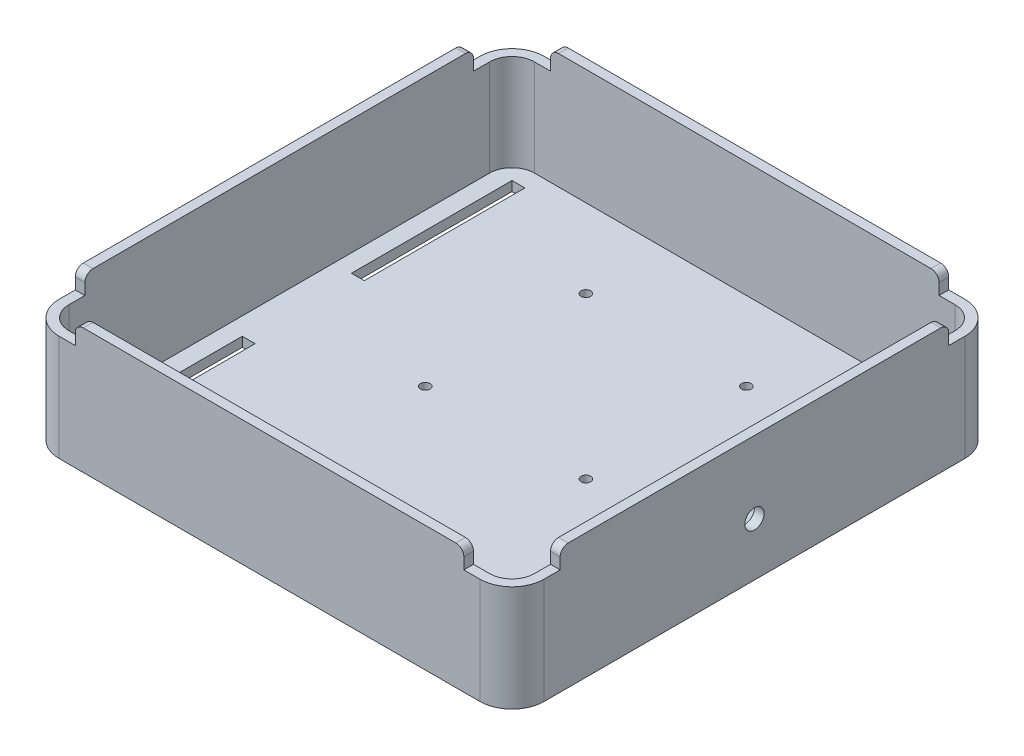
SolidWorks part; units mm, degrees
ref_plane "Front Plane" through (0, 0, 0) normal (0, 0, 1) x (1, 0, 0)
ref_plane "Top Plane" through (0, 0, 0) normal (0, 1, 0) x (1, 0, 0)
ref_plane "Right Plane" through (0, 0, 0) normal (1, 0, 0) x (0, 0, -1)
sketch "Sketch1" plane through (0, 0, 0) normal (0, 1, 0) x (1, 0, 0)
  line L1 (-75.5, 75.5) -> (75.5, 75.5)
  line L2 (-75.5, 75.5) -> (-75.5, -75.5)
  line L3 (-75.5, -75.5) -> (75.5, -75.5)
  line L4 (75.5, 75.5) -> (75.5, -75.5)
  line L5 (-75.5, 75.5) -> (75.5, -75.5) construction
  line L6 (-75.5, -75.5) -> (75.5, 75.5) construction
  point P0 (0, 0)
  dimension "D1" = 151
extrude "Boss-Extrude1" add sketch "Sketch1" along normal mid plane 33
sketch "Sketch2" plane through (0, 16.5, 0) normal (0, 1, 0) x (1, 0, 0)
  line L0 (75.5, 75.5) -> (-75.5, 75.5) construction
  line L1 (-72.5, 72.5) -> (72.5, 72.5)
  line L2 (-72.5, 72.5) -> (-72.5, -72.5)
  line L3 (-72.5, -72.5) -> (72.5, -72.5)
  line L4 (72.5, 72.5) -> (72.5, -72.5)
  line L5 (-72.5, 72.5) -> (72.5, -72.5) construction
  line L6 (-72.5, -72.5) -> (72.5, 72.5) construction
  point P0 (0, 0)
  dimension "D1" = 3
extrude "Cut-Extrude1" cut sketch "Sketch2" against normal offset from surface (30 mm away) 3 up to face at (0, -16.5, 0)
sketch "Sketch3" plane through (0, -13.5, 0) normal (0, 1, 0) x (1, 0, 0)
  line L0 (-67, 71) -> (-67, 67) construction
  line L1 (-67, -17) -> (-63, -17)
  line L2 (-67, -17) -> (-67, -67)
  line L3 (-67, -67) -> (-63, -67)
  line L4 (-63, -17) -> (-63, -67)
  line L5 (-67, -17) -> (-63, -67) construction
  line L6 (-67, -67) -> (-63, -17) construction
  line L7 (72.5, 0) -> (-72.5, 0) construction
  line L8 (-72.5, 72.5) -> (-72.5, -72.5) construction
  line L9 (-67, 67) -> (-63, 67)
  line L10 (-63, 17) -> (-63, 67)
  line L11 (-67, 17) -> (-63, 17)
  line L12 (-67, 17) -> (-67, 67)
  line L13 (-71, 71) -> (71, 71) construction
  line L14 (-71, 71) -> (-71, -71) construction
  line L15 (-71, -71) -> (71, -71) construction
  line L16 (71, 71) -> (71, -71) construction
  line L17 (-71, 71) -> (71, -71) construction
  line L18 (-71, -71) -> (71, 71) construction
  line L19 (-67, 67) -> (-71, 67) construction
  point P0 (-65, -42)
  point P6 (0, 0)
  point P14 (0, 0)
  dimension "D1" = 4
  dimension "D2" = 142
  dimension "D3" = 50
  dimension "D4" = 4
extrude "Cut-Extrude2" cut sketch "Sketch3" against normal through all
mirror "Mirror1" about plane through (0, 0, 0) normal (1, 0, 0) of "Cut-Extrude2"
sketch "Sketch4" plane through (0, -13.5, 0) normal (0, 1, 0) x (1, 0, 0)
  circle A0 centre (0, 0) radius 21.5
  dimension "D1" = 43
sketch "Sketch6" plane through (0, 16.5, 0) normal (0, 1, 0) x (1, 0, 0)
  line L0 (-72.5, -72.5) -> (72.5, -72.5) construction
  line L1 (-60.5, -72.5) -> (60.5, -72.5)
  line L2 (-60.5, -72.5) -> (-60.5, -75.5)
  line L3 (-60.5, -75.5) -> (60.5, -75.5)
  line L4 (60.5, -72.5) -> (60.5, -75.5)
  line L5 (-75.5, -75.5) -> (75.5, -75.5) construction
  line L6 (-75.5, -75.5) -> (-60.5, -75.5) construction
  line L7 (60.5, -75.5) -> (75.5, -75.5) construction
  dimension "D1" = 15
extrude "Boss-Extrude2" add sketch "Sketch6" along normal blind 6
mirror "Mirror2" about plane through (0, 0, 0) normal (0, 0, 1) of "Boss-Extrude2"
sketch "Sketch7" plane through (0, 16.5, 0) normal (0, 1, 0) x (1, 0, 0)
  line L0 (-75.5, 75.5) -> (-75.5, -75.5) construction
  line L1 (-75.5, 60.5) -> (-72.5, 60.5)
  line L2 (-75.5, 60.5) -> (-75.5, -60.5)
  line L3 (-75.5, -60.5) -> (-72.5, -60.5)
  line L4 (-72.5, 60.5) -> (-72.5, -60.5)
  line L5 (-72.5, 72.5) -> (-72.5, -72.5) construction
  line L6 (-75.5, 75.5) -> (-75.5, 60.5) construction
  line L7 (-75.5, -60.5) -> (-75.5, -75.5) construction
  dimension "D1" = 15
extrude "Boss-Extrude3" add sketch "Sketch7" along normal up to surface (6 mm away) up to face at (0, 22.5, -74)
mirror "Mirror4" about plane through (0, 0, 0) normal (1, 0, 0) of "Boss-Extrude3"
sketch "Sketch8" plane through (75.5, 0, 0) normal (1, 0, 0) x (0, 0, -1)
  circle A0 centre (0, 0) radius 3
  dimension "D1" = 6
extrude "Cut-Extrude3" cut sketch "Sketch8" against normal up to next
sketch "Sketch10" plane through (-75.5, 0, 0) normal (-1, 0, 0) x (0, 0, 1)
  circle A0 centre (0, 0) radius 14
  dimension "D1" = 28
fillet "Fillet1" radius 10 4 edges at (75.5, 0, -75.5) (-75.5, 0, -75.5) (75.5, 0, 75.5) (-75.5, 0, 75.5)
fillet "Fillet2" radius 7 4 edges at (-72.5, 1.5, 72.5) (72.5, 1.5, 72.5) (72.5, 1.5, -72.5) (-72.5, 1.5, -72.5)
fillet "Fillet3" radius 2.5 8 edges at (60.5, 22.5, -74) (-60.5, 22.5, -74) (-74, 22.5, -60.5) (-74, 22.5, 60.5) (74, 22.5, -60.5) (74, 22.5, 60.5) (60.5, 22.5, 74) (-60.5, 22.5, 74)
sketch "Sketch11" plane through (0, -13.5, 0) normal (0, 1, 0) x (1, 0, 0)
  line L0 (-71, 60.5402) -> (-67.2507, 60.5402)
  line L1 (-71, 71) -> (71, 71) construction
  line L2 (-71, 71) -> (-71, -71) construction
  line L3 (-71, -71) -> (71, -71) construction
  line L4 (71, 71) -> (71, -71) construction
  line L5 (-71, 71) -> (71, -71) construction
  line L6 (-71, -71) -> (71, 71) construction
  point P0 (0, 0)
  dimension "D1" = 142
sketch "Sketch12" plane through (0, -16.5, 0) normal (0, -1, 0) x (1, 0, 0)
  line L0 (0, 71) -> (0, 27) construction
  line L1 (-71, 71) -> (71, 71) construction
  line L3 (25, 52) -> (-25, 52) construction
  line L4 (25, 52) -> (25, 2) construction
  line L5 (25, 2) -> (-25, 2) construction
  line L6 (-25, 52) -> (-25, 2) construction
  line L7 (25, 52) -> (-25, 2) construction
  line L8 (25, 2) -> (-25, 52) construction
  circle A0 centre (-25, 52) radius 1.5
  circle A1 centre (-25, 2) radius 1.5
  circle A2 centre (25, 52) radius 1.5
  circle A3 centre (25, 2) radius 1.5
  circle A4 centre (-25, -48) radius 1.5
  circle A5 centre (25, -48) radius 1.5
  dimension "D3" = 3
  dimension "D1" = 44
  dimension "D2" = 50
  dimension "D4" = 50
extrude "Cut-Extrude4" cut sketch "Sketch12" against normal through all
